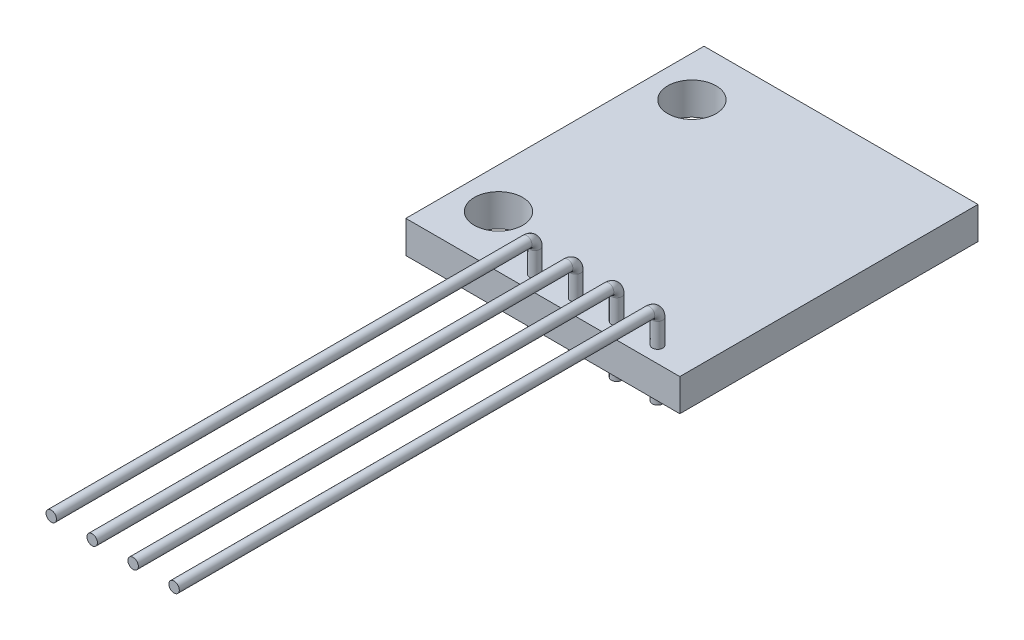
SolidWorks part; units mm, degrees
ref_plane "Front Plane" through (0, 0, 0) normal (0, 0, 1) x (1, 0, 0)
ref_plane "Top Plane" through (0, 0, 0) normal (0, 1, 0) x (1, 0, 0)
ref_plane "Right Plane" through (0, 0, 0) normal (1, 0, 0) x (0, 0, -1)
sketch "Sketch1" plane through (0, 0, 0) normal (0, 1, 0) x (1, 0, 0)
  line L0 (2.5, 15.25) -> (2.5, 3.25) construction
  line L1 (0, 0) -> (17, 0)
  line L2 (0, 0) -> (0, 18.5)
  line L3 (0, 18.5) -> (17, 18.5)
  line L4 (17, 0) -> (17, 18.5)
  line L5 (2.5, 3.25) -> (2.5, 0) construction
  line L6 (2.5, 15.25) -> (2.5, 18.5) construction
  line L7 (2.5, 9.25) -> (0, 9.25) construction
  circle A0 centre (2.5, 15.25) radius 1.5
  circle A1 centre (2.5, 3.25) radius 1.5
  dimension "D3" = 3
  dimension "D4" = 3
  dimension "D1" = 17
  dimension "D2" = 18.5
  dimension "D5" = 2.5
  dimension "D6" = 12
extrude "Boss-Extrude1" add sketch "Sketch1" along normal blind 2
ref_plane "Plane1" through (7, 0, 0) normal (-1, 0, 0) x (0, 0, 1)
sketch "Sketch2" plane through (7, 0, 0) normal (-1, 0, 0) x (0, 0, 1)
  line L0 (-1, -1) -> (-1, 3.5)
  line L1 (-0.5, 4) -> (29, 4)
  line L2 (0, 2) -> (0, 0) construction
  line L3 (-18.5, 2) -> (0, 2) construction
  line L4 (-18.5, 0) -> (0, 0) construction
  arc A0 (-1, 3.5) -> (-0.5, 4) centre (-0.5, 3.5) cw
  dimension "D4" = 0.5
  dimension "D1" = 1
  dimension "D2" = 2
  dimension "D3" = 1
  dimension "D5" = 30
sketch "Sketch3" plane through (0, 2, 0) normal (0, 1, 0) x (1, 0, 0)
  line L2 (7, 1) -> (7, 0.5) construction
  line L3 (7, 1.1) -> (7, -1.1) construction
  line L4 (0, 0) -> (17, 0) construction
  circle A0 centre (7, 1) radius 0.325
  dimension "D1" = 0.65
  dimension "D2" = 1
sweep "Sweep1" add profiles "Sketch3" path "Sketch2"
pattern_linear "LPattern1" count 4 spacing 2.54 along (1, 0, 0) of "Sweep1"
equation "\"D4@Sketch1\"=\"D3@Sketch1\""
